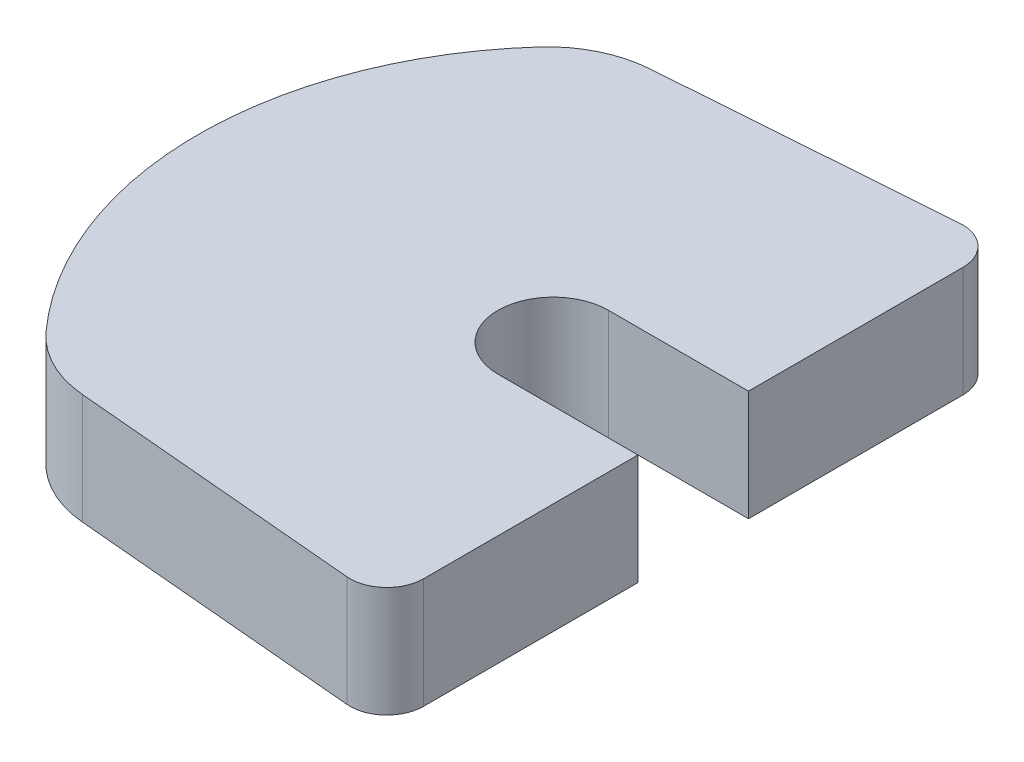
SolidWorks part; units mm, degrees
ref_plane "Front Plane" through (0, 0, 0) normal (0, 0, 1) x (1, 0, 0)
ref_plane "Top Plane" through (0, 0, 0) normal (0, 1, 0) x (1, 0, 0)
ref_plane "Right Plane" through (0, 0, 0) normal (1, 0, 0) x (0, 0, -1)
sketch "Sketch1" plane through (0, 0, 0) normal (0, 1, 0) x (1, 0, 0)
  line L0 (0, 0) -> (3.8, 0)
  line L1 (3.8, 0) -> (3.8, -5.8158)
  line L2 (2.7121, -6.8119) -> (-5.1636, -6.1169)
  line L3 (-5.12, 9.2359) -> (2.7266, 9.8131)
  line L4 (3.8, 8.8158) -> (3.8, 3)
  line L5 (3.8, 3) -> (0, 3)
  arc A0 (-7.1284, -5.1369) -> (-7.1284, 8.2524) centre (0.3, 1.5577) cw
  arc A1 (0, 3) -> (0, 0) centre (0, 1.5) ccw
  arc A2 (3.8, -5.8158) -> (2.7121, -6.8119) centre (2.8, -5.8158) cw
  arc A3 (2.7266, 9.8131) -> (3.8, 8.8158) centre (2.8, 8.8158) cw
  arc A4 (-5.1636, -6.1169) -> (-7.1284, -5.1369) centre (-4.8999, -3.1285) cw
  arc A5 (-7.1284, 8.2524) -> (-5.12, 9.2359) centre (-4.8999, 6.244) cw
  point P11 (0, 0)
  point P12 (-9.7, 1.5577)
  point P15 (3.8, -6.9079)
  point P18 (3.8, 9.8921)
  point P21 (-6.221, -6.0236)
  point P24 (-6.2008, 9.1564)
  point P25 (0, 0)
  dimension "D2" = 1.5
  dimension "D5" = 1
  dimension "D6" = 3
  dimension "D8" = 10
  dimension "D1" = 13.5
  dimension "D3" = 16.8
  dimension "D4" = 15.18
  dimension "D9" = 3.8
  dimension "D10" = 4.207
extrude "Boss-Extrude1" add sketch "Sketch1" along normal blind 3
